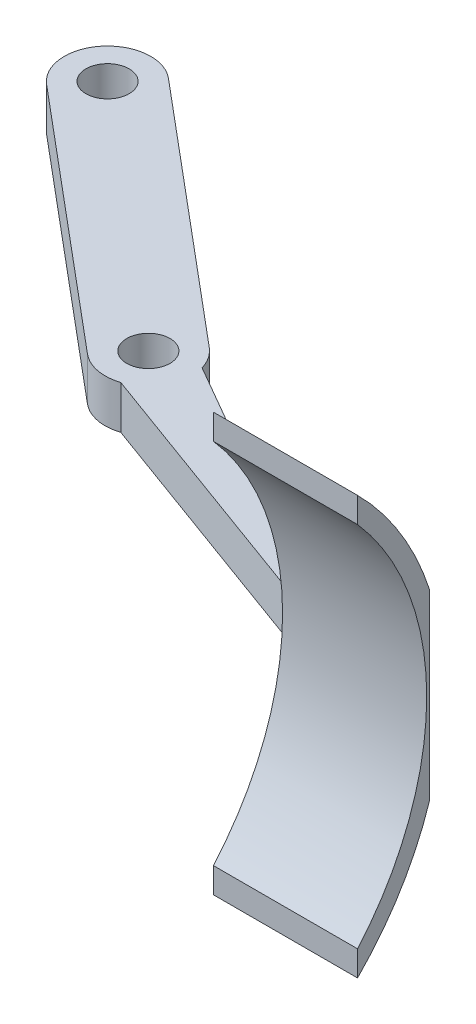
SolidWorks part; units mm, degrees
ref_plane "前视基准面" through (0, 0, 0) normal (0, 0, 1) x (1, 0, 0)
ref_plane "上视基准面" through (0, 0, 0) normal (0, 1, 0) x (1, 0, 0)
ref_plane "右视基准面" through (0, 0, 0) normal (1, 0, 0) x (0, 0, -1)
other "Configuration Table"
sketch "草图1" plane through (0, 0, 0) normal (0, 1, 0) x (1, 0, 0)
  line L0 (0, 0) -> (25, 0) construction
  line L1 (0, 3) -> (25, 3)
  line L2 (0, -3) -> (25, -3)
  arc A0 (0, 3) -> (0, -3) centre (0, 0) ccw
  arc A1 (25, -3) -> (25, 3) centre (25, 0) ccw
  circle A2 centre (0, 0) radius 1.5
  circle A3 centre (25, 0) radius 1.5
  point P3 (12.5, 0)
  dimension "D3" = 3
  dimension "D4" = 3
  dimension "D1" = 25
  dimension "D2" = 6
extrude "凸台-拉伸1" add sketch "草图1" along normal blind 3
sketch "草图2" plane through (0, 0, 0) normal (0, -1, 0) x (1, 0, 0)
  line L0 (26.5, -2.5981) -> (46.0069, 8.6643)
  line L1 (46.0069, 8.6643) -> (56.0069, 8.6643)
  line L2 (25, -3) -> (0, -3) construction
  line L3 (25.5182, 2.9549) -> (26.9424, 2.7051)
  line L4 (26.9424, 2.7051) -> (46.0069, 9.6643)
  line L5 (46.0069, 9.6643) -> (56.0069, 9.6643)
  line L6 (56.0069, 9.6643) -> (56.0069, 8.6643)
  arc A0 (25, -3) -> (25, 3) centre (25, 0) ccw construction
  arc A1 (26.5, -2.5981) -> (25.5182, 2.9549) centre (25, 0) ccw
  dimension "D2" = 150
  dimension "D3" = 10
  dimension "D4" = 1
  dimension "D5" = 150
extrude "凸台-拉伸2" add sketch "草图2" against normal blind 3
sketch "草图3" plane through (56.0069, 0, 0) normal (1, 0, 0) x (0, 0, -1)
  line L5 (-14.6643, 16) -> (-14.6643, 14.2452)
  line L12 (-9.6643, 3) -> (-9.6643, 0) construction
  line L14 (-13.4643, 12.7317) -> (-13.4643, -9.7317) construction
  line L15 (-14.6643, -11.2452) -> (-14.6643, -13)
  line L16 (-14.6643, 16) -> (-14.6643, -13) construction
  arc A2 (-14.6643, 16) -> (-14.6643, -13) centre (-29.1851, 1.5) cw
  arc A3 (-14.6643, 14.2452) -> (-14.6643, -11.2452) centre (-29.1851, 1.5) cw
  arc A4 (-13.4643, 12.7317) -> (-13.4643, -9.7317) centre (-29.1851, 1.5) cw construction
  dimension "D1" = 1.2
  dimension "D3" = 5
extrude "凸台-拉伸3" add sketch "草图3" against normal blind 10
sketch "草图4" plane through (0, 3, 0) normal (0, 1, 0) x (1, 0, 0)
  line L0 (38.753, -4.4762) -> (51.0069, -8.7192)
  line L1 (26.5, 2.5981) -> (46.0069, -8.6643) construction
  line L2 (56.0069, -8.7192) -> (46.0069, -8.7192) construction
  line L3 (51.0069, -8.7192) -> (46.0069, -8.6643)
  line L4 (46.0069, -8.6643) -> (38.753, -4.4762)
extrude "凸台-拉伸4" add sketch "草图4" against normal blind 3
sketch "草图5" plane through (0, 0, 8.6643) normal (0, 0, -1) x (-1, 0, 0)
  line L4 (-50.8484, 0) -> (-50.8484, 3)
  line L5 (-50.8484, 3) -> (-56.0069, 3)
  line L6 (-56.0069, 3) -> (-56.0069, 0)
  line L7 (-56.0069, 0) -> (-50.8484, 0)
  line L8 (-50.8484, 0) -> (-50.8484, 3)
  line L9 (-50.8484, 3) -> (-56.0069, 3)
  line L10 (-56.0069, 3) -> (-56.0069, 0)
  line L11 (-56.0069, 0) -> (-50.8484, 0)
  dimension "D1" = 0
extrude "凸台-拉伸5" add sketch "草图5" along normal blind 2
sketch "草图6" plane through (0, 0, 6.6643) normal (0, 0, -1) x (-1, 0, 0)
  line L0 (-50.8484, 0) -> (-38.753, 0) construction
  line L1 (-50.8484, 3) -> (-43.8484, 3)
  line L2 (-50.8484, 3) -> (-50.8484, 0)
  line L3 (-50.8484, 0) -> (-43.8484, 0)
  line L4 (-43.8484, 3) -> (-43.8484, 0)
  dimension "D1" = 7
extrude "凸台-拉伸6" add sketch "草图6" against normal blind 2
chamfer "倒角1" distance 3 angle 45 1 edges at (56.0069, 1.5, 6.6643)
sketch "草图7" plane through (0, 0, 0) normal (0, -1, 0) x (1, 0, 0)
  line L1 (-39.5225, 22.1068) -> (27.0776, 22.1068)
  line L2 (-39.5225, 22.1068) -> (-39.5225, -6.8652)
  line L3 (-39.5225, -6.8652) -> (27.0776, -6.8652)
  line L4 (27.0776, 22.1068) -> (27.0776, -6.8652)
  line L5 (-39.5225, 22.1068) -> (27.0776, -6.8652) construction
  line L6 (-39.5225, -6.8652) -> (27.0776, 22.1068) construction
  point P0 (-6.2225, 7.6208)
extrude "切除-拉伸1" cut sketch "草图7" against normal blind 80
sketch "草图8" plane through (0, 0, 0) normal (0, -1, 0) x (1, 0, 0)
  line L0 (27.0776, 0.2449) -> (9.4586, -14.5392) construction
  line L1 (27.0776, -2.2646) -> (27.0776, 2.7545) construction
  line L2 (29.006, -2.0532) -> (11.3869, -16.8373)
  line L3 (25.1492, 2.5431) -> (7.5302, -12.241)
  line L4 (27.0776, 2.7545) -> (27.0776, -2.2646) construction
  arc A0 (29.006, -2.0532) -> (25.1492, 2.5431) centre (27.0776, 0.2449) ccw
  arc A1 (7.5302, -12.241) -> (11.3869, -16.8373) centre (9.4586, -14.5392) ccw
  point P4 (18.2681, -7.1471)
  dimension "D1" = 23
  dimension "D2" = 6
  dimension "D3" = 50
extrude "凸台-拉伸8" add sketch "草图8" against normal blind 3
sketch "草图10" plane through (0, 3, 0) normal (0, 1, 0) x (1, 0, 0)
  circle A0 centre (9.4586, 14.5392) radius 1.5
  circle A1 centre (27.0776, -0.2449) radius 1.5
  dimension "D1" = 3
  dimension "D2" = 3
extrude "切除-拉伸2" cut sketch "草图10" against normal blind 3
